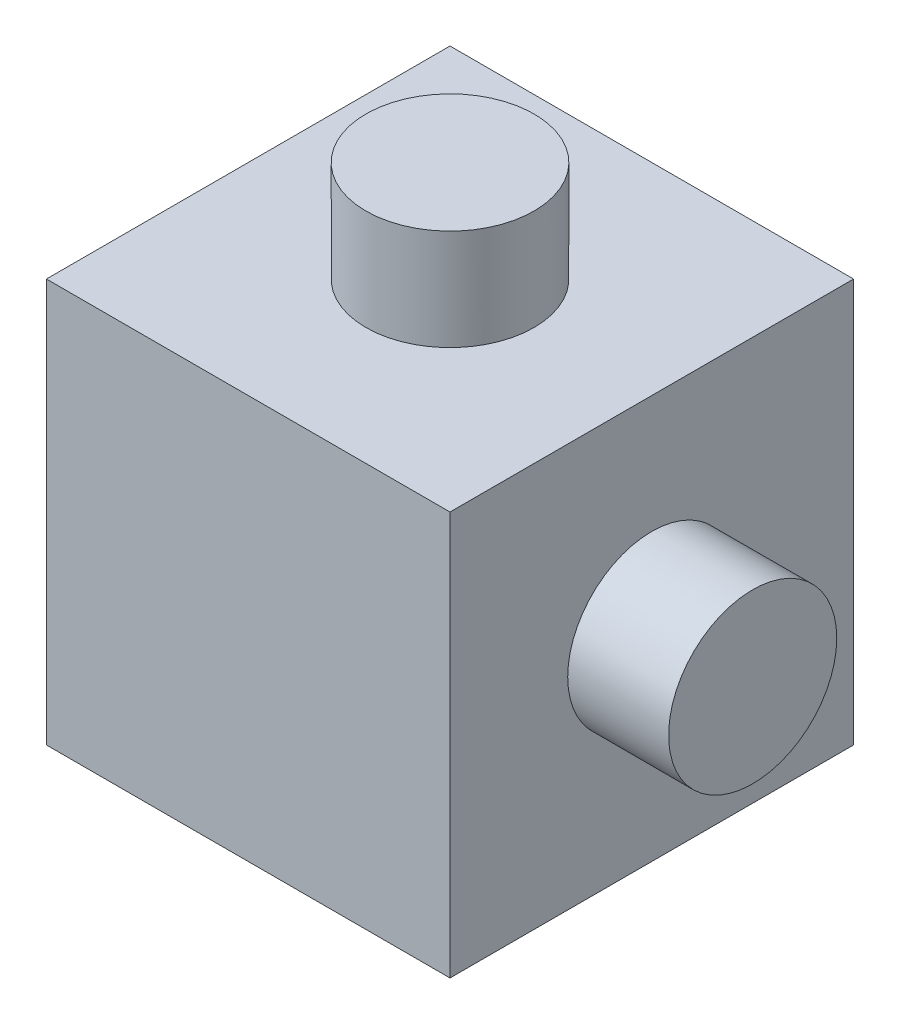
SolidWorks part; units mm, degrees
ref_plane "前视基准面" through (0, 0, 0) normal (0, 0, 1) x (1, 0, 0)
ref_plane "上视基准面" through (0, 0, 0) normal (0, 1, 0) x (1, 0, 0)
ref_plane "右视基准面" through (0, 0, 0) normal (1, 0, 0) x (0, 0, -1)
sketch "草图1" plane through (0, 0, 0) normal (0, 1, 0) x (1, 0, 0)
  line L1 (-6, -6) -> (6, -6)
  line L2 (-6, -6) -> (-6, 6)
  line L3 (-6, 6) -> (6, 6)
  line L4 (6, -6) -> (6, 6)
  line L5 (-6, -6) -> (6, 6) construction
  line L6 (-6, 6) -> (6, -6) construction
  point P0 (0, 0)
  dimension "D1" = 12
  dimension "D2" = 12
extrude "凸台-拉伸1" add sketch "草图1" along normal blind 12
sketch "草图2" plane through (0, 12, 0) normal (0, 1, 0) x (1, 0, 0)
  circle A0 centre (0, 0) radius 2.5
  dimension "D1" = 5
extrude "凸台-拉伸2" add sketch "草图2" along normal blind 3 and the other way blind 15
sketch "草图3" plane through (6, 0, 0) normal (1, 0, 0) x (0, 0, -1)
  line L0 (-6, 0) -> (6, 0) construction
  circle A0 centre (0, 6) radius 2.5
  dimension "D1" = 5
  dimension "D2" = 6
extrude "凸台-拉伸3" add sketch "草图3" along normal blind 3 and the other way blind 15
